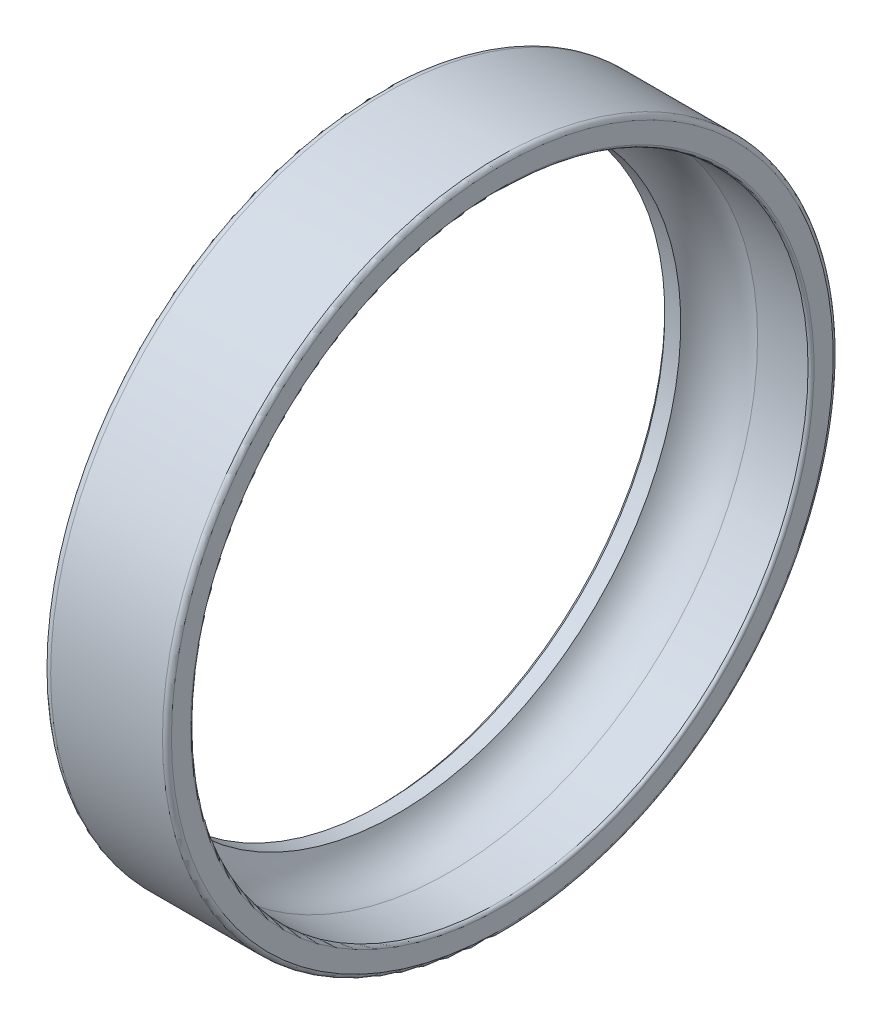
SolidWorks part; units mm, degrees
ref_plane "Piano frontale" through (0, 0, 0) normal (0, 0, 1) x (1, 0, 0)
ref_plane "Piano superiore" through (0, 0, 0) normal (0, 1, 0) x (1, 0, 0)
ref_plane "Piano destro" through (0, 0, 0) normal (1, 0, 0) x (0, 0, -1)
ref_plane "Piano1" through (0, 0, 0) normal (0, 0, 1) x (1, 0, 0)
sketch "Schizzo1" plane through (0, 0, 0) normal (0, 0, 1) x (1, 0, 0)
  line L0 (0, 64.35) -> (1, 63.35)
  line L1 (1, 63.35) -> (4.5613, 63.35)
  line L2 (16.0396, 69.05) -> (27.3333, 69.05)
  line L3 (28, 69.7167) -> (28, 74)
  line L4 (27, 75) -> (2, 75)
  line L5 (0, 73) -> (0, 64.35)
  line L6 (28, 0) -> (0, 0) construction
  arc A0 (4.5613, 63.35) -> (16.0396, 69.05) centre (14, 58.75) cw
  arc A1 (27.3333, 69.05) -> (28, 69.7167) centre (27.3333, 69.7167) ccw
  arc A2 (28, 74) -> (27, 75) centre (27, 74) ccw
  arc A3 (2, 75) -> (0, 73) centre (2, 73) ccw
revolve "Rivoluzione1" add sketch "Schizzo1" angle 360 about L6
